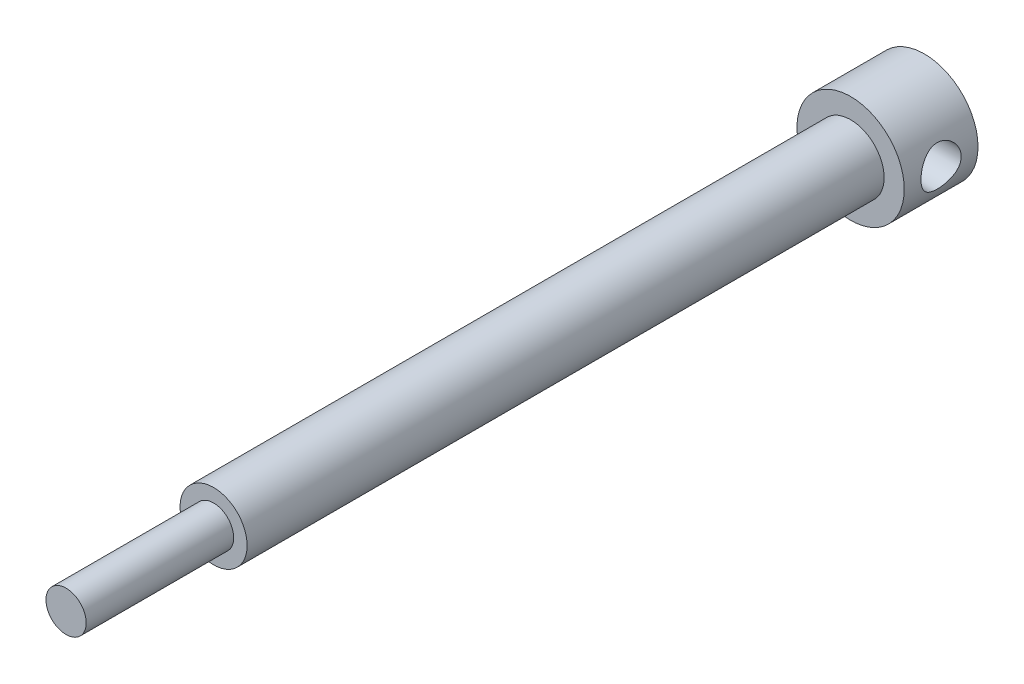
SolidWorks part; units mm, degrees
ref_plane "Piano frontale" through (0, 0, 0) normal (0, 0, 1) x (1, 0, 0)
ref_plane "Piano superiore" through (0, 0, 0) normal (0, 1, 0) x (1, 0, 0)
ref_plane "Piano destro" through (0, 0, 0) normal (1, 0, 0) x (0, 0, -1)
sketch "Schizzo1" plane through (0, 0, 0) normal (0, 0, 1) x (1, 0, 0)
  circle A0 centre (0, 0) radius 8
  dimension "D1" = 16
extrude "Estrusione-Estrusione1" add sketch "Schizzo1" along normal blind 11
sketch "Schizzo2" plane through (0, 0, 11) normal (0, 0, 1) x (1, 0, 0)
  circle A0 centre (0, 0) radius 5
  dimension "D1" = 10
extrude "Estrusione-Estrusione2" add sketch "Schizzo2" along normal blind 95
cosmetic thread "Filettatura cosmetica1" parameters "D2"=8.344
sketch "Schizzo3" plane through (0, 0, 106) normal (0, 0, 1) x (1, 0, 0)
  circle A0 centre (0, 0) radius 3
  dimension "D1" = 6
extrude "Estrusione-Estrusione3" add sketch "Schizzo3" along normal blind 22
sketch "Schizzo4" plane through (0, 0, 0) normal (1, 0, 0) x (0, 0, -1)
  line L0 (0, 0) -> (-11, 0) construction
  line L1 (-11, 5) -> (-11, -5) construction
  line L2 (-5.5, 0) -> (-5.5, 8) construction
  line L3 (0, 8) -> (-11, 8) construction
  line L4 (-5.5, 0) -> (-5.5, -8) construction
  line L5 (-11, -8) -> (0, -8) construction
  circle A0 centre (-5.5, 0) radius 3
  dimension "D1" = 6
extrude "Taglio-Estrusione1" cut sketch "Schizzo4" against normal mid plane 16
